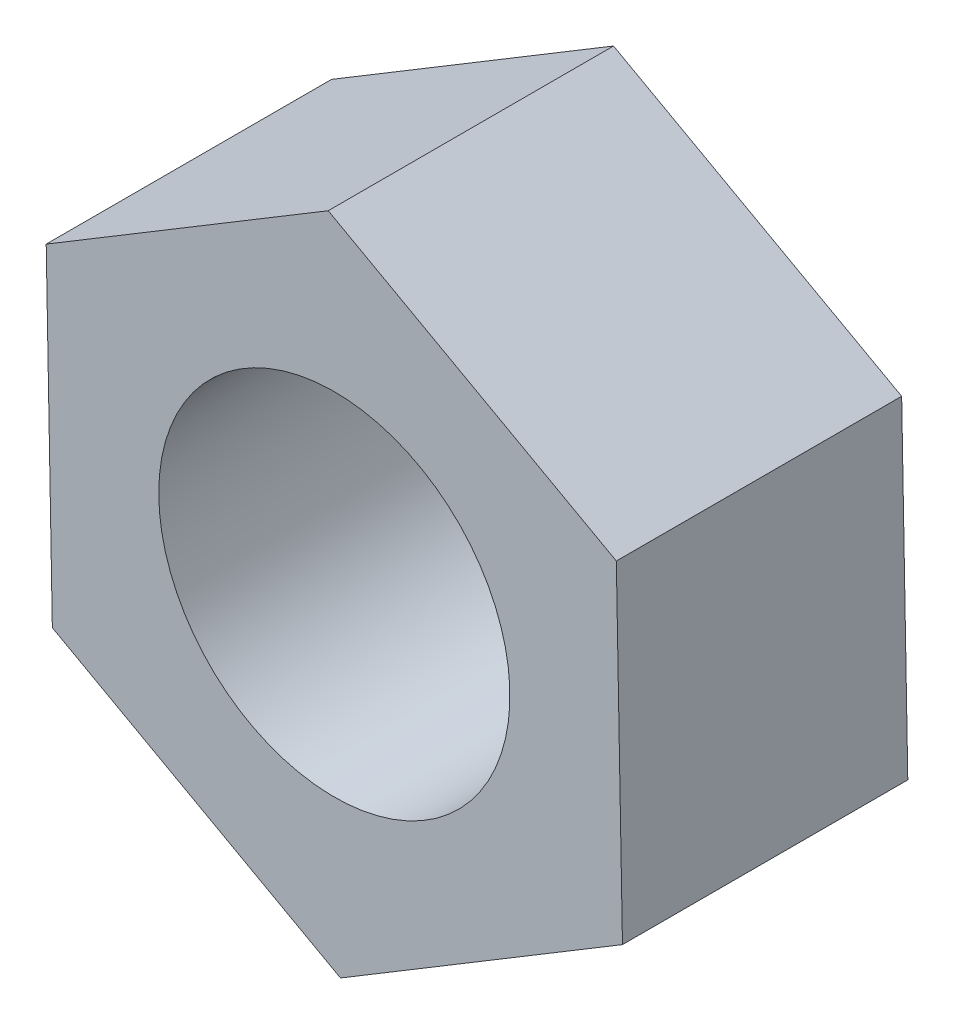
SolidWorks part; units mm, degrees
material "Plain Carbon Steel"
ref_plane "Front Plane" through (0, 0, 0) normal (0, 0, 1) x (1, 0, 0)
ref_plane "Top Plane" through (0, 0, 0) normal (0, 1, 0) x (1, 0, 0)
ref_plane "Right Plane" through (0, 0, 0) normal (1, 0, 0) x (0, 0, -1)
sketch "Sketch1" plane through (0, 0, 0) normal (0, 0, 1) x (1, 0, 0)
  line L1 (-6.564, 3.6282) -> (-6.4241, -3.8705)
  line L2 (-6.4241, -3.8705) -> (0.1399, -7.4987)
  line L3 (0.1399, -7.4987) -> (6.564, -3.6282)
  line L4 (6.564, -3.6282) -> (6.4241, 3.8705)
  line L5 (6.4241, 3.8705) -> (-0.1399, 7.4987)
  line L6 (-0.1399, 7.4987) -> (-6.564, 3.6282)
  circle A0 centre (0, 0) radius 7.5 construction
  circle A1 centre (0, 0) radius 4
  dimension "D1" = 15
  dimension "D2" = 8
extrude "Boss-Extrude1" add sketch "Sketch1" along normal blind 6.5
